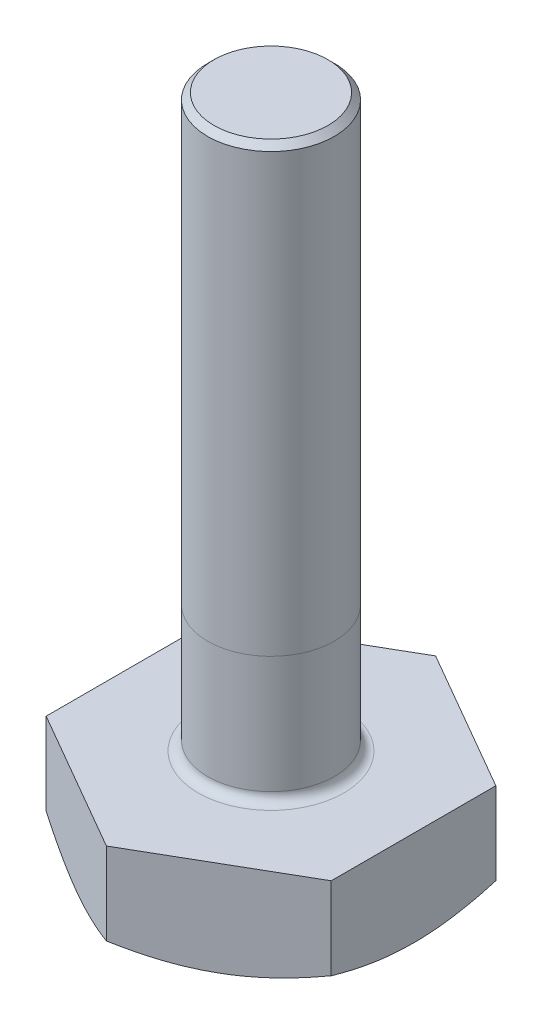
SolidWorks part; units mm, degrees
ref_plane "Front Plane" through (0, 0, 0) normal (0, 0, 1) x (1, 0, 0)
ref_plane "Top Plane" through (0, 0, 0) normal (0, 1, 0) x (1, 0, 0)
ref_plane "Right Plane" through (0, 0, 0) normal (1, 0, 0) x (0, 0, -1)
sketch "Sketch1" plane through (0, 0, 0) normal (0, 1, 0) x (1, 0, 0)
  line L1 (0, -2.5981) -> (2.25, -1.299)
  line L2 (2.25, -1.299) -> (2.25, 1.299)
  line L3 (2.25, 1.299) -> (0, 2.5981)
  line L4 (0, 2.5981) -> (-2.25, 1.299)
  line L5 (-2.25, 1.299) -> (-2.25, -1.299)
  line L6 (-2.25, -1.299) -> (0, -2.5981)
  circle A0 centre (0, 0) radius 2.25 construction
  circle A1 centre (0, 0) radius 1 construction
  dimension "D1" = 4.5
  dimension "D2" = 2
extrude "Boss-Extrude1" add sketch "Sketch1" along normal blind 1.5
sketch "Sketch3" plane through (0, 0, 0) normal (0, 1, 0) x (1, 0, 0)
  circle A0 centre (0, 0) radius 2.25 construction
  circle A1 centre (0, 0) radius 2.25
extrude "Cut-Extrude1" cut sketch "Sketch3" along normal blind 1.5 draft 60 flip side to cut
sketch "Sketch4" plane through (0, 1.5, 0) normal (0, 1, 0) x (1, 0, 0)
  circle A0 centre (0, 0) radius 1
extrude "Boss-Extrude2" add sketch "Sketch4" along normal blind 9
chamfer "Chamfer1" distance 0.1 angle 45 1 edges at (0, 10.5, 1)
fillet "Fillet1" radius 0.15 1 edges at (0, 1.5, 1)
sketch "Sketch5" plane through (0, 0, 0) normal (0, 0, 1) x (1, 0, 0)
  line L0 (-3.8043, 3.5) -> (3.8043, 3.5)
  line L1 (0.9, 10.5) -> (-0.9, 10.5) construction
  point P2 (0, 3.5)
  dimension "D1" = 7
split line "Split Line1"
